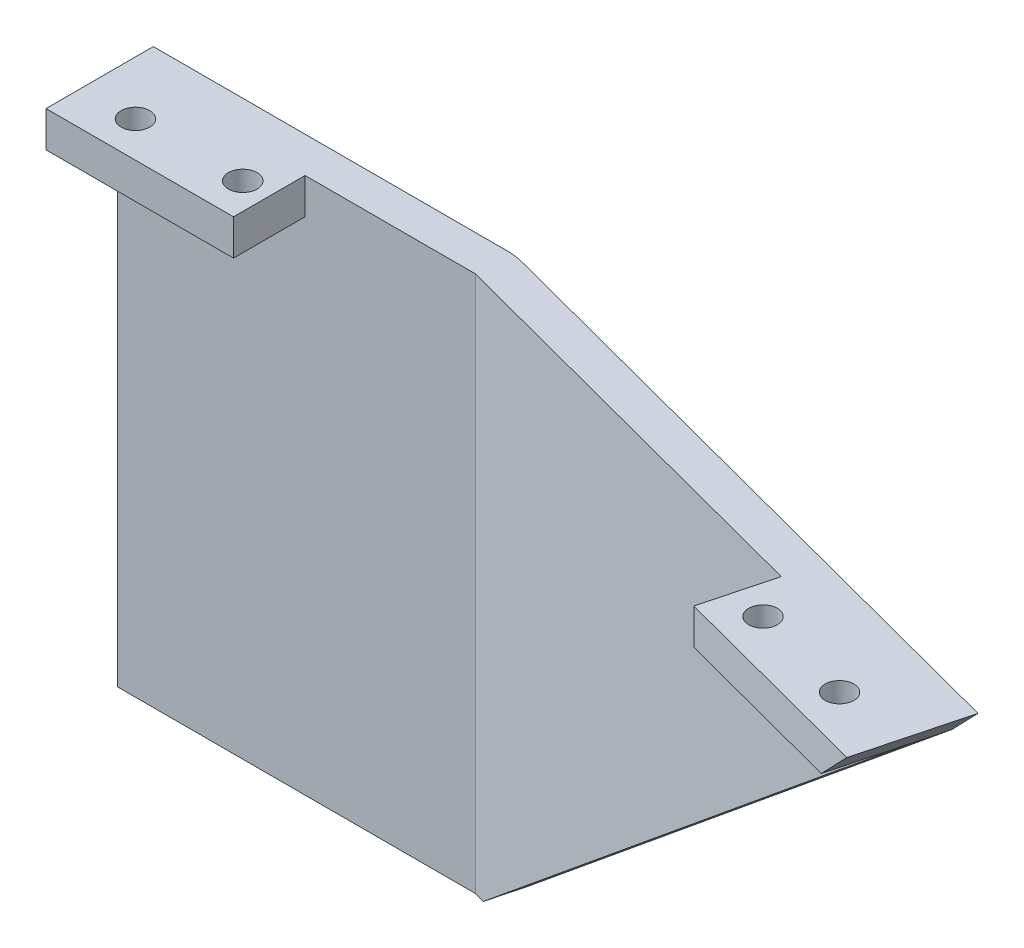
SolidWorks part; units mm, degrees
ref_plane "前视基准面" through (0, 0, 0) normal (0, 0, 1) x (1, 0, 0)
ref_plane "上视基准面" through (0, 0, 0) normal (0, 1, 0) x (1, 0, 0)
ref_plane "右视基准面" through (0, 0, 0) normal (1, 0, 0) x (0, 0, -1)
sketch "草图1" plane through (0, 0, 0) normal (0, 0, 1) x (1, 0, 0)
  line L1 (-25, 75) -> (25, 75)
  line L2 (-25, 75) -> (-25, -75)
  line L3 (-25, -75) -> (25, -75)
  line L4 (25, 75) -> (25, -75)
  line L5 (0, -75) -> (0, 75) construction
  line L6 (-25, 0) -> (25, 0) construction
  point P0 (0, 0)
  dimension "D1" = 150
  dimension "D2" = 50
extrude "凸台-拉伸1" add sketch "草图1" along normal blind 10
sketch "草图2" plane through (25, 0, 0) normal (1, 0, 0) x (0, 0, -1)
  line L1 (-10, 75) -> (0, 75)
  line L2 (-10, 75) -> (-10, -75)
  line L3 (-10, -75) -> (0, -75)
  line L4 (0, 75) -> (0, -75)
sketch "草图3" plane through (0, 75, 0) normal (0, 1, 0) x (1, 0, 0)
  line L0 (-13, 0) -> (25, -10)
  line L1 (25, 0) -> (-25, 0) construction
  dimension "D1" = 12
ref_plane "基准面1" through (25, 75, 10) normal (0.9671, 0, 0.2545) x (0.2545, 0, -0.9671)
sketch "草图4" plane through (25, 75, 10) normal (0.9671, 0, 0.2545) x (0.2545, 0, -0.9671)
  line L5 (0, 0) -> (0, -150)
  line L6 (0, -150) -> (10, -150)
  line L7 (10, -150) -> (10, 0)
  line L8 (10, 0) -> (0, 0)
  dimension "D1" = 10
extrude "凸台-拉伸2" add sketch "草图4" along normal blind 280
sketch "草图5" plane through (25.842, 0, 6.8005) normal (-0.9671, 0, -0.2545) x (-0.2545, 0, 0.9671)
  line L1 (-6.6916, 75) -> (3.3084, 75)
  line L2 (-6.6916, 75) -> (-6.6916, -75)
  line L3 (-6.6916, -75) -> (3.3084, -75)
  line L4 (3.3084, 75) -> (3.3084, -75)
loft "放样1" add profiles "草图2", "草图5"
sketch "草图7" plane through (0, 75, 0) normal (0, 1, 0) x (1, 0, 0)
  line L0 (25, -10) -> (295.7809, -81.2581)
  line L1 (-25, -10) -> (25, -10)
  line L2 (-25, -10) -> (-25, -30)
  line L3 (-25, -30) -> (22.4125, -30)
  line L6 (295.7809, -81.2581) -> (290.691, -100.5996)
  line L7 (22.4125, -30) -> (290.691, -100.5996)
  dimension "D1" = 20
  dimension "D2" = 20
extrude "凸台-拉伸3" add sketch "草图7" against normal blind 10
sketch "草图8" plane through (-0.842, 0, 3.1995) normal (-0.2545, 0, 0.9671) x (0.9671, 0, 0.2545)
  line L1 (26.7218, -77.6469) -> (-24.1769, -75)
  line L7 (196.7218, 65) -> (26.7218, -77.6469)
  line L8 (306.7218, 65) -> (26.7218, 65) construction
  line L9 (26.7218, -75) -> (26.7218, 65) construction
  line L11 (393.4504, 75.4988) -> (350.3034, -101.8809)
  line L12 (350.3034, -101.8809) -> (84.8173, -109.1745)
  line L13 (84.8173, -109.1745) -> (27.6357, -109.1745)
  line L15 (27.6357, -109.1745) -> (-24.1769, -75)
  line L16 (196.7218, 65) -> (253.2271, 121.3013)
  line L17 (253.2271, 121.3013) -> (354.4892, 81.5738)
  line L18 (354.4892, 81.5738) -> (393.4504, 75.4988)
  dimension "D1" = 40
  dimension "D2" = 110
extrude "切除-拉伸2" cut sketch "草图8" against normal mid plane 100
sketch "草图10" plane through (-25, 0, 0) normal (-1, 0, 0) x (0, 0, 1)
  line L6 (0, 75) -> (0, -75)
  line L7 (0, -75) -> (10, -75)
  line L8 (10, -75) -> (10, 65)
  line L9 (10, 65) -> (30, 65)
  line L10 (30, 65) -> (30, 75)
  line L11 (30, 75) -> (0, 75)
  line L12 (0, 75) -> (0, -75)
  line L14 (10, -75) -> (10, 65)
  line L15 (10, 65) -> (30, 65)
  line L16 (30, 65) -> (30, 75)
  line L17 (30, 75) -> (0, 75)
  line L18 (0, -75) -> (10, -75)
  dimension "D1" = 0
extrude "凸台-拉伸4" add sketch "草图10" along normal blind 50
sketch "草图11" plane through (0, 65, 0) normal (0, -1, 0) x (1, 0, 0)
  line L0 (177.187, 60.3897) -> (148.1748, 52.7549) construction
  line L1 (189.4027, 53.2639) -> (25, 10) construction
  line L2 (-75, 30) -> (22.4125, 30) construction
  line L3 (189.4027, 53.2639) -> (184.3128, 72.6054) construction
  line L4 (-75, 10) -> (-75, 30) construction
  line L5 (22.4125, 30) -> (184.3128, 72.6054) construction
  circle A0 centre (-60, 20) radius 4
  circle A1 centre (177.187, 60.3897) radius 4
  circle A2 centre (148.1748, 52.7549) radius 4
  circle A3 centre (-30, 20) radius 4
  dimension "D1" = 8
  dimension "D2" = 8
  dimension "D4" = 8
  dimension "D9" = 8
  dimension "D3" = 10
  dimension "D5" = 10
  dimension "D6" = 10
  dimension "D7" = 30
  dimension "D8" = 15
  dimension "D10" = 30
extrude "切除-拉伸3" cut sketch "草图11" against normal blind 30
sketch "草图12" plane through (0, 75, 0) normal (0, 1, 0) x (1, 0, 0)
  line L0 (-22.5875, -30) -> (-22.5875, -10)
  line L1 (-75, -30) -> (22.4125, -30) construction
  line L2 (-22.5875, -10) -> (25, -10)
  line L3 (25, -10) -> (141.0489, -40.5392)
  line L4 (141.0489, -40.5392) -> (135.9591, -59.8807)
  line L5 (22.4125, -30) -> (194.0186, -75.1595) construction
  line L6 (135.9591, -59.8807) -> (22.4125, -30)
  line L7 (22.4125, -30) -> (-22.5875, -30)
  dimension "D1" = 20
  dimension "D2" = 20
  dimension "D4" = 120
  dimension "D5" = 45
extrude "切除-拉伸4" cut sketch "草图12" against normal blind 10
